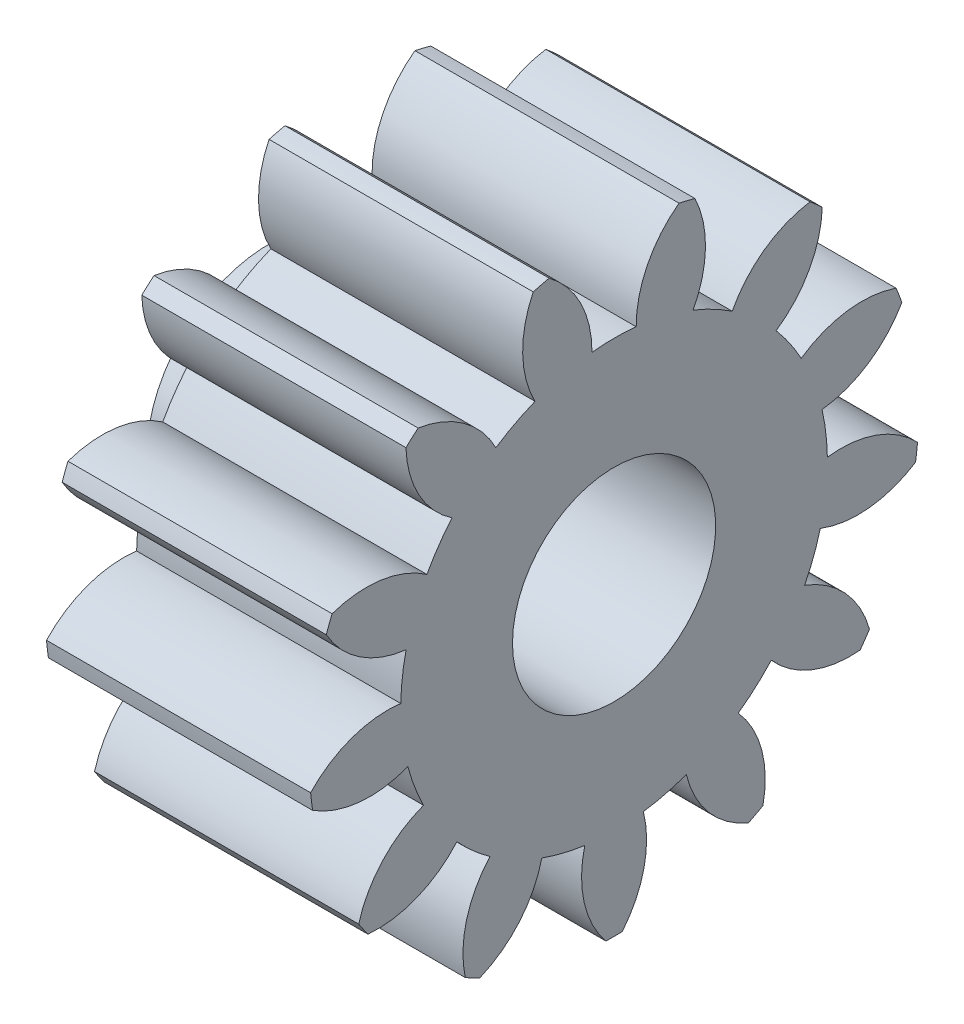
SolidWorks part; units mm, degrees
ref_plane "Plane1" through (0, 0, 0) normal (0, 0, 1) x (1, 0, 0)
ref_plane "Plane2" through (0, 0, 0) normal (0, 1, 0) x (1, 0, 0)
ref_plane "Plane3" through (0, 0, 0) normal (1, 0, 0) x (0, 0, -1)
other "Configuration Table"
sketch "HoldingSke" plane through (0, 0, 0) normal (0, 1, 0) x (1, 0, 0)
  line L0 (0, 0) -> (0.4872, -0.1125)
  line L1 (-15, 0) -> (100, 0) construction
  line L2 (0, 0) -> (-2.1039, 2.3779)
  line L3 (0, 0) -> (-11.863, 4.5341)
  line L4 (0, 0) -> (8.4147, 1.9427)
  line L5 (0, 0) -> (-15.9282, -5.9407)
  line L6 (0, 0) -> (-10.7765, -7.2709)
  line L7 (-2.1039, 2.3779) -> (1.5554, 18.9794)
  line L8 (-76.2, 54.61) -> (-74.4, 54.61)
  line L9 (-71.009, 38.7566) -> (-53.1078, 45.2721)
  line L10 (-76.2, 71.12) -> (104.1128, 71.12)
  line L11 (0, 0) -> (-13, 0)
  line L12 (-76.2, 101.6) -> (-76.133, 101.6)
  line L13 (24.9733, 27.94) -> (52.9518, 28.4284)
  line L14 (24.9733, 27.94) -> (24.9743, 27.94)
  line L15 (24.9733, 27.94) -> (100.4006, 29.5858)
  line L16 (-63.627, -2) -> (-12.827, -2)
  circle A0 centre (0, 0) radius 5
  circle A1 centre (0, 0) radius 6
  circle A2 centre (0, 0) radius 6
  circle A3 centre (0, 0) radius 5
  dimension "MHD" = 12
  dimension "Hub_dia" = 12
  dimension "Bore" = 10
  dimension "MBD" = 10
  dimension "Num_teeth" = 13
  dimension "Pitch" = 0.5
  dimension "Overall_len" = 17
  dimension "Show_teeth" = 13
  dimension "Thickness" = 13
  dimension "OAL" = 17.0001
  dimension "T_dim" = 1.8
  dimension "Ap" = 20
  dimension "H" = 19.05
  dimension "Pitch_radius" = 180.3128
  dimension "Width" = 13
  dimension "Backlash" = 0.067
  dimension "Addendum_fac" = 1
  dimension "Dedendum_fac" = 1.25
  dimension "Clearance_fac" = 0.25
  dimension "Dedendum_add" = 0.001
  dimension "Module" = 2
sketch "BasProSke" plane through (0, 0, 0) normal (0, 1, 0) x (1, 0, 0)
  line L0 (-10, 0) -> (60, 0) construction
  line L1 (0, 0) -> (0, 15)
  line L2 (0, 0) -> (13, 0)
  line L3 (13, 0) -> (13, 15)
  line L4 (13, 15) -> (0, 15)
  dimension "Thickness" = 13
  dimension "Diameter" = 30
revolve "Base-Revolve" add sketch "BasProSke" angle 360 about L0
sketch "TooCutSke" plane through (0, 0, 0) normal (1, 0, 0) x (0, 0, -1)
  line L1 (0, 0) -> (0, 107) construction
  line L2 (0, 0) -> (-1.6841, 12.8905) construction
  line L3 (0, 0) -> (-6.1834, 25.087) construction
  line L4 (-1.6841, 12.8905) -> (-3.0917, 12.5435) construction
  arc A0 (1.0882, 10.4424) -> (-1.0882, 10.4424) centre (0, 0) ccw
  arc A1 (3.2249, 14.6752) -> (-3.2249, 14.6752) centre (0, 0) ccw
  circle A2 centre (0, 0) radius 13 construction
  circle A3 centre (0, 0) radius 12.216 construction
  arc A4 (-1.0882, 10.4424) -> (-3.2249, 14.6752) centre (-6.2882, 10.4733) ccw
  arc A5 (3.2249, 14.6752) -> (1.0882, 10.4424) centre (6.2882, 10.4733) ccw
  dimension "Root_dia" = 20.998
  dimension "Overcut_dia" = 30.0508
  dimension "Pitch_dia" = 26
  dimension "Base_dia" = 24.432
  dimension "Flank_rad" = 5.2
  dimension "Half_ang" = 13.846
  dimension "Half_CT" = 1.4497
extrude "ToothCut" cut sketch "TooCutSke" along normal through all
fillet "Breaks" [suppressed] radius 0.04
fillet "RootFillets" [suppressed] radius 0.501
pattern_circular "TeethCuts" count 13 every 27.692 about axis through (-10, 0, 0) along (1, 0, 0) of "ToothCut", "RootFillets", "Breaks"
sketch "HubNeaOneSke" plane through (0, 0, 0) normal (-1, 0, 0) x (0, 0, 1)
  circle A0 centre (0, 0) radius 6
  dimension "Diameter" = 12
extrude "HubNearOne" add sketch "HubNeaOneSke" along normal blind 4.0001
sketch "HubNeaBotSke" plane through (0, 0, 0) normal (-1, 0, 0) x (0, 0, 1)
  circle A0 centre (0, 0) radius 6
  dimension "Diameter" = 12
extrude "HubNearBoth" [suppressed] add sketch "HubNeaBotSke" along normal blind 2
ref_plane "FarPln" through (13, 0, 0) normal (1, 0, 0) x (0, 0, -1)
sketch "HubFarSke" plane through (13, 0, 0) normal (1, 0, 0) x (0, 0, -1)
  circle A0 centre (0, 0) radius 6
  dimension "Diameter" = 12
extrude "HubFar" [suppressed] add sketch "HubFarSke" along normal blind 2
sketch "BorSke" plane through (0, 0, 0) normal (1, 0, 0) x (0, 0, -1)
  circle A0 centre (0, 0) radius 5
  dimension "Diameter" = 10
extrude "Bore" cut sketch "BorSke" along normal mid plane 34.0001
sketch "KeySke" plane through (0, 0, 0) normal (1, 0, 0) x (0, 0, -1)
  line L0 (-2, 0) -> (-2, 6.8)
  line L1 (-2, 6.8) -> (2, 6.8)
  line L2 (2, 6.8) -> (2, 0)
  line L3 (0, 0) -> (0, 34) construction
  line L4 (-2, 0) -> (2, 0)
  dimension "Offset" = 6.8
  dimension "Width" = 4
extrude "Keyway" [suppressed] cut sketch "KeySke" along normal mid plane 34.0001
pattern_circular "Keyway2" [suppressed] count 2 every 90 about axis through (-10, 0, 0) along (1, 0, 0)
scale "Scale1" scale about centroid uniform scaling yes scale factor 0.317565
equation "' \"Module@HoldingSke\" = 6.35"
equation "' \"Num_teeth@HoldingSke\" = 12"
equation "' \"Ap@HoldingSke\" =  20"
equation "' \"Ap@HoldingSke\" = 20"
equation "' \"Width@HoldingSke\" = 0.5 * 25.4"
equation "' \"Hub_dia@HoldingSke\"= 1 * 25.4"
equation "' \"Hub_dia@HoldingSke\" = 1 * 25.4"
equation "' \"Overall_len@HoldingSke\" = 1.0 * 25.4"
equation "' \"Bore@HoldingSke\" = 0.75 * 25.4"
equation "' \"T_dim@HoldingSke\" = 0.1 * 25.4"
equation "' \"Width@KeySke\" = 0.25 * 25.4"
equation "' \"Show_teeth@HoldingSke\" = 13"
equation "' \"Backlash@HoldingSke\" = 0.009 * 25.4"
equation "' \"Addendum_fac@HoldingSke\" = 1.0"
equation "' \"Dedendum_fac@HoldingSke\" = 1.25"
equation "' \"Dedendum_add@HoldingSke\" = 0.00005 * 25.4"
equation "' \"Clearance_fac@HoldingSke\" = 0.25"
equation "\"Pitch@HoldingSke\" = 1 / \"Module@HoldingSke\""
equation "\"Overcut_dia@TooCutSke\" = (\"Num_teeth@HoldingSke\" + 2 * \"Addendum_fac@HoldingSke\") / \"Pitch@HoldingSke\" + 0.002 * 25.4"
equation "\"Pitch_dia@TooCutSke\" = \"Num_teeth@HoldingSke\" / \"Pitch@HoldingSke\""
equation "\"Base_dia@TooCutSke\" = \"Num_teeth@HoldingSke\" / \"Pitch@HoldingSke\" * cos((\"Ap@HoldingSke\"  * 3.14159265 / 180))"
equation "\"Root_dia@TooCutSke\" = (\"Num_teeth@HoldingSke\" + 2) / \"Pitch@HoldingSke\" - 2 * (\"Addendum_fac@HoldingSke\" + \"Dedendum_fac@HoldingSke\") / \"Pitch@HoldingSke\" - \"Dedendum_add@HoldingSke\" * 2"
equation "\"Half_ang@TooCutSke\" = 180 / \"Num_teeth@HoldingSke\""
equation "\"Half_CT@TooCutSke\" = \"Num_teeth@HoldingSke\" / \"Pitch@HoldingSke\" * sin((3.14159265 / 2 / \"Num_teeth@HoldingSke\")) / 2 - 7 * \"Backlash@HoldingSke\" / 4"
equation "\"Flank_rad@TooCutSke\" = \"Num_teeth@HoldingSke\" / \"Pitch@HoldingSke\" / 5"
equation "\"Radius@RootFillets\" = \"Clearance_fac@HoldingSke\" / \"Pitch@HoldingSke\" + \"Dedendum_add@HoldingSke\""
equation "\"Break_rad@Breaks\" = 0.02 / \"Pitch@HoldingSke\""
equation "\"Thickness@HoldingSke\" = \"Width@HoldingSke\""
equation "\"OAL@HoldingSke\" = \"Thickness@HoldingSke\""
equation "\"MHD@HoldingSke\" = (\"Num_teeth@HoldingSke\" + 2) / \"Pitch@HoldingSke\" - 2 * (\"Addendum_fac@HoldingSke\" + \"Dedendum_fac@HoldingSke\")  / \"Pitch@HoldingSke\" - \"Dedendum_add@HoldingSke\" * 2"
equation "\"MBD@HoldingSke\" = (\"Num_teeth@HoldingSke\" + 2) / \"Pitch@HoldingSke\" - 2 * (\"Addendum_fac@HoldingSke\" + \"Dedendum_fac@HoldingSke\")  / \"Pitch@HoldingSke\" - \"Dedendum_add@HoldingSke\" * 2 - 0.002 * 25.4"
equation "\"MHD@HoldingSke\" = ((sgn( \"MHD@HoldingSke\" - \"Hub_dia@HoldingSke\" )-1)*( \"MHD@HoldingSke\" - \"Hub_dia@HoldingSke\" ))/-2+ \"Hub_dia@HoldingSke\""
equation "\"MBD@HoldingSke\" = ((sgn( \"MBD@HoldingSke\" - \"Bore@HoldingSke\" )-1)*( \"MBD@HoldingSke\" - \"Bore@HoldingSke\" ))/-2+ \"Bore@HoldingSke\""
equation "\"OAL@HoldingSke\" = ((sgn( \"OAL@HoldingSke\" - \"Overall_len@HoldingSke\" )+1)*( \"OAL@HoldingSke\" - \"Overall_len@HoldingSke\" ))/2 + \"Overall_len@HoldingSke\" + 0.000002 * 25.4"
equation "\"Num_teeth@TeethCuts\" = int( \"Show_teeth@HoldingSke\" ) + 1"
equation "\"Num_teeth@TeethCuts\" = ((sgn( \"Num_teeth@TeethCuts\" - \"Num_teeth@HoldingSke\" )-1)*( \"Num_teeth@TeethCuts\" - \"Num_teeth@HoldingSke\" ))/-2+ \"Num_teeth@HoldingSke\""
equation "\"Num_teeth@TeethCuts\" = ((sgn( \"Num_teeth@TeethCuts\" - 2.0)+1)*( \"Num_teeth@TeethCuts\" - 2.0))/2 +2.0"
equation "\"Angle@TeethCuts\" = 360.0 / \"Num_teeth@HoldingSke\""
equation "\"Diameter@BasProSke\" = (\"Num_teeth@HoldingSke\" + 2 * \"Addendum_fac@HoldingSke\") / \"Pitch@HoldingSke\""
equation "\"Thickness@BasProSke\"  = \"Thickness@HoldingSke\""
equation "' \"Fillet_rad@BasProSke\" =  \"Thickness@HoldingSke\" * 0.05"
equation "' \"Fillet_rad@BasProSke\" = \"Thickness@HoldingSke\" * 0.05"
equation "\"MHD@HoldingSke\" = ((sgn( \"MHD@HoldingSke\" - \"Root_dia@TooCutSke\" )-1)*( \"MHD@HoldingSke\" - \"Root_dia@TooCutSke\" ))/-2+ \"Root_dia@TooCutSke\""
equation "\"Diameter@HubNeaOneSke\" = \"MHD@HoldingSke\""
equation "\"Length@HubNearOne\" = \"OAL@HoldingSke\" - \"Thickness@BasProSke\""
equation "\"Diameter@HubNeaBotSke\" = \"MHD@HoldingSke\""
equation "\"Length@HubNearBoth\" = ( \"OAL@HoldingSke\" - \"Thickness@BasProSke\" ) / 2.0"
equation "\"Thickness@FarPln\" = \"Thickness@BasProSke\""
equation "\"Diameter@HubFarSke\" = \"MHD@HoldingSke\""
equation "\"Length@HubFar\" = ( \"OAL@HoldingSke\" - \"Thickness@BasProSke\" ) / 2.0"
equation "\"Diameter@BorSke\" = \"MBD@HoldingSke\""
equation "\"D1@Bore\" = \"OAL@HoldingSke\" * 2.0"
equation "\"D1@Keyway\" = \"OAL@HoldingSke\" * 2.0"
equation "\"Offset@KeySke\" = \"T_dim@HoldingSke\" + \"MBD@HoldingSke\" / 2.0"
